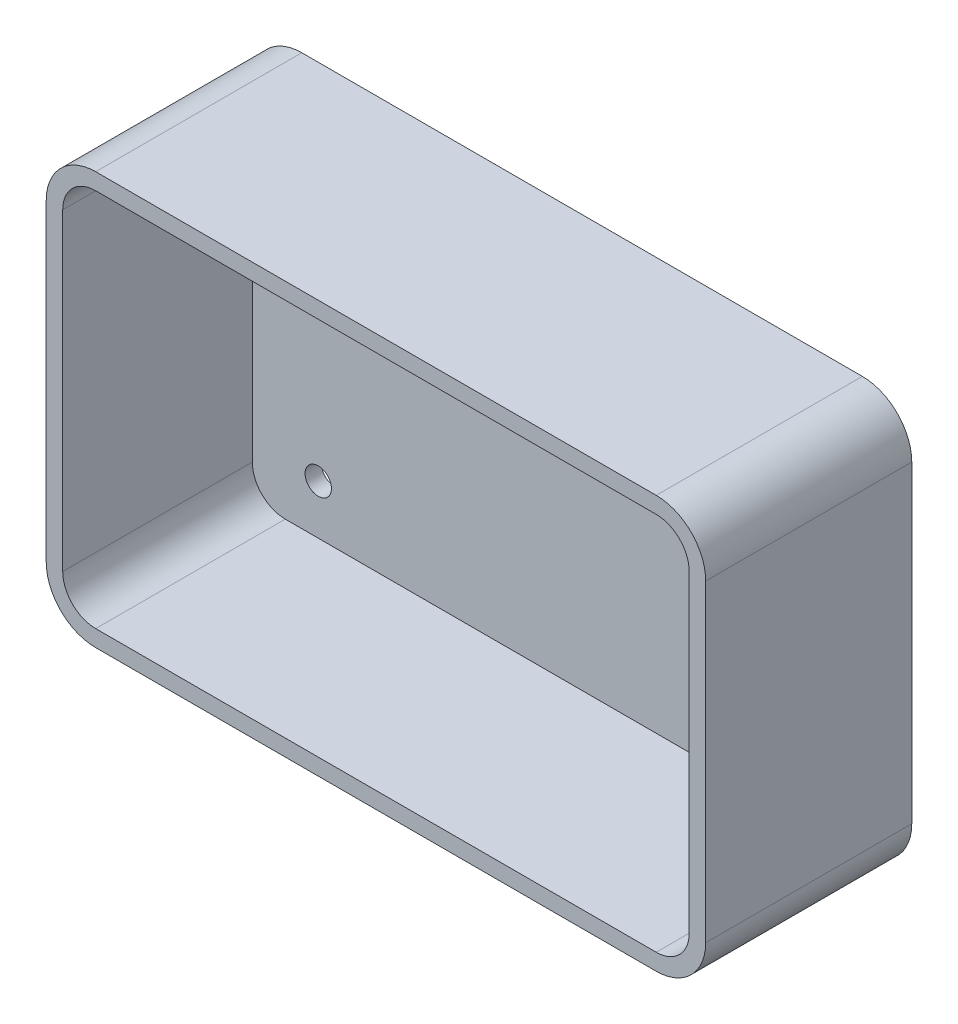
SolidWorks part; units mm, degrees
ref_plane "Front Plane" through (0, 0, 0) normal (0, 0, 1) x (1, 0, 0)
ref_plane "Top Plane" through (0, 0, 0) normal (0, 1, 0) x (1, 0, 0)
ref_plane "Right Plane" through (0, 0, 0) normal (1, 0, 0) x (0, 0, -1)
sketch "Sketch1" plane through (0, 0, 0) normal (0, 0, 1) x (1, 0, 0)
  line L0 (-34, -25) -> (34, -25)
  line L1 (40, -19) -> (40, 19)
  line L2 (34, 25) -> (-34, 25)
  line L3 (-40, 19) -> (-40, -19)
  arc A0 (34, -25) -> (40, -19) centre (34, -19) ccw
  arc A1 (40, 19) -> (34, 25) centre (34, 19) ccw
  arc A2 (-34, 25) -> (-40, 19) centre (-34, 19) ccw
  arc A3 (-40, -19) -> (-34, -25) centre (-34, -19) ccw
extrude "Body_Block" add sketch "Sketch1" along normal blind 25
shell "Body_Shell" thickness 2
sketch "Sketch2" plane through (0, 0, 0) normal (0, 0, 1) x (1, 0, 0)
  circle A0 centre (-30, -17) radius 1.6
  circle A1 centre (-30, 17) radius 1.6
  circle A2 centre (30, -17) radius 1.6
  circle A3 centre (30, 17) radius 1.6
extrude "Floor_Holes" cut sketch "Sketch2" against normal through all and the other way through all
equation "\"length\" = 80mm"
equation "\"width\" = 50mm"
equation "\"height\" = 25mm"
equation "\"corner_radius\" = 6mm"
equation "\"wall\" = 2mm"
equation "\"hole_d\" = 3.2mm"
equation "\"hole_dx\" = 30mm"
equation "\"hole_dy\" = 17mm"
equation "\"D1@Body_Block\" = \"height\""
equation "\"D1@Body_Shell\" = \"wall\""
